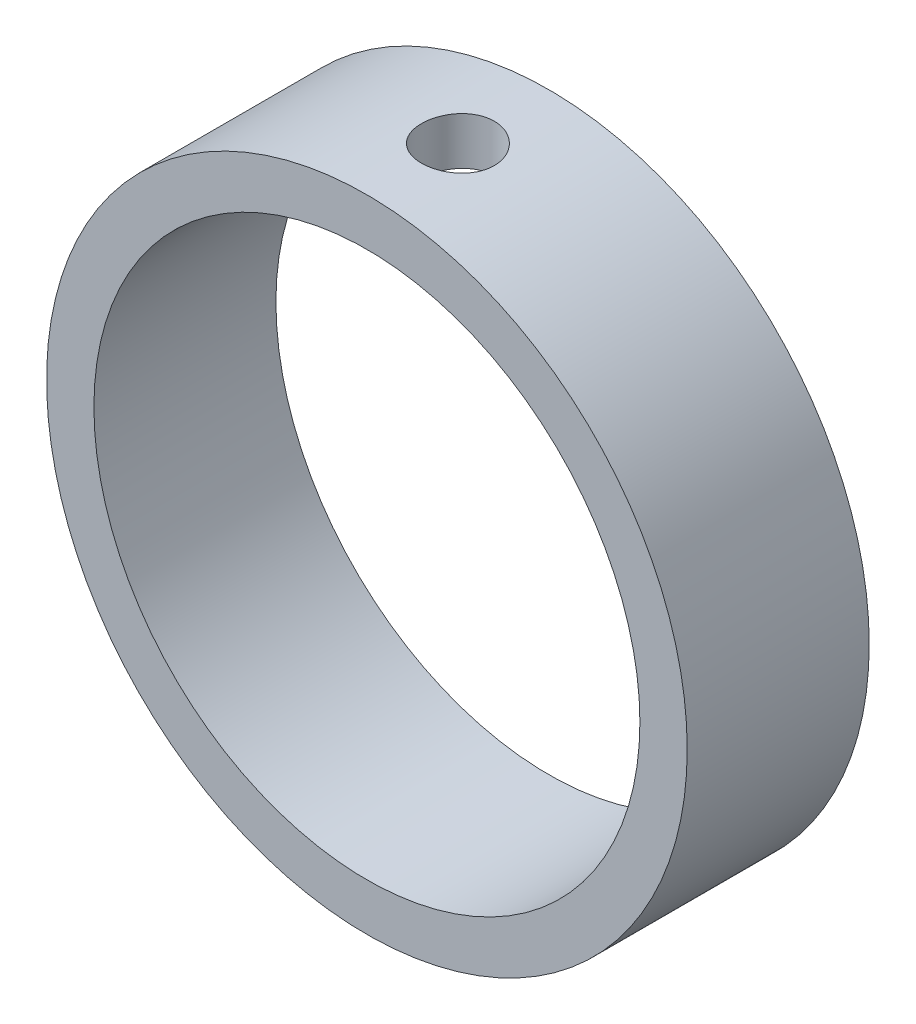
SolidWorks part; units mm, degrees
material "ASTM A36 Steel"
ref_plane "Front Plane" through (0, 0, 0) normal (0, 0, 1) x (1, 0, 0)
ref_plane "Top Plane" through (0, 0, 0) normal (0, 1, 0) x (1, 0, 0)
ref_plane "Right Plane" through (0, 0, 0) normal (1, 0, 0) x (0, 0, -1)
sketch "Sketch1" plane through (0, 0, 0) normal (0, 0, 1) x (1, 0, 0)
  circle A0 centre (0, 0) radius 44
  circle A1 centre (0, 0) radius 37.5
  dimension "D1" = 88
  dimension "D2" = 75
extrude "Boss-Extrude1" add sketch "Sketch1" along normal blind 25
sketch "Sketch2" plane through (0, 0, 0) normal (0, 1, 0) x (1, 0, 0)
  line L0 (37.5, 0) -> (-37.5, 0) construction
  circle A0 centre (0, -12.5) radius 5
  dimension "D1" = 10
  dimension "D2" = 12.5
extrude "Cut-Extrude1" cut sketch "Sketch2" along normal blind 70
